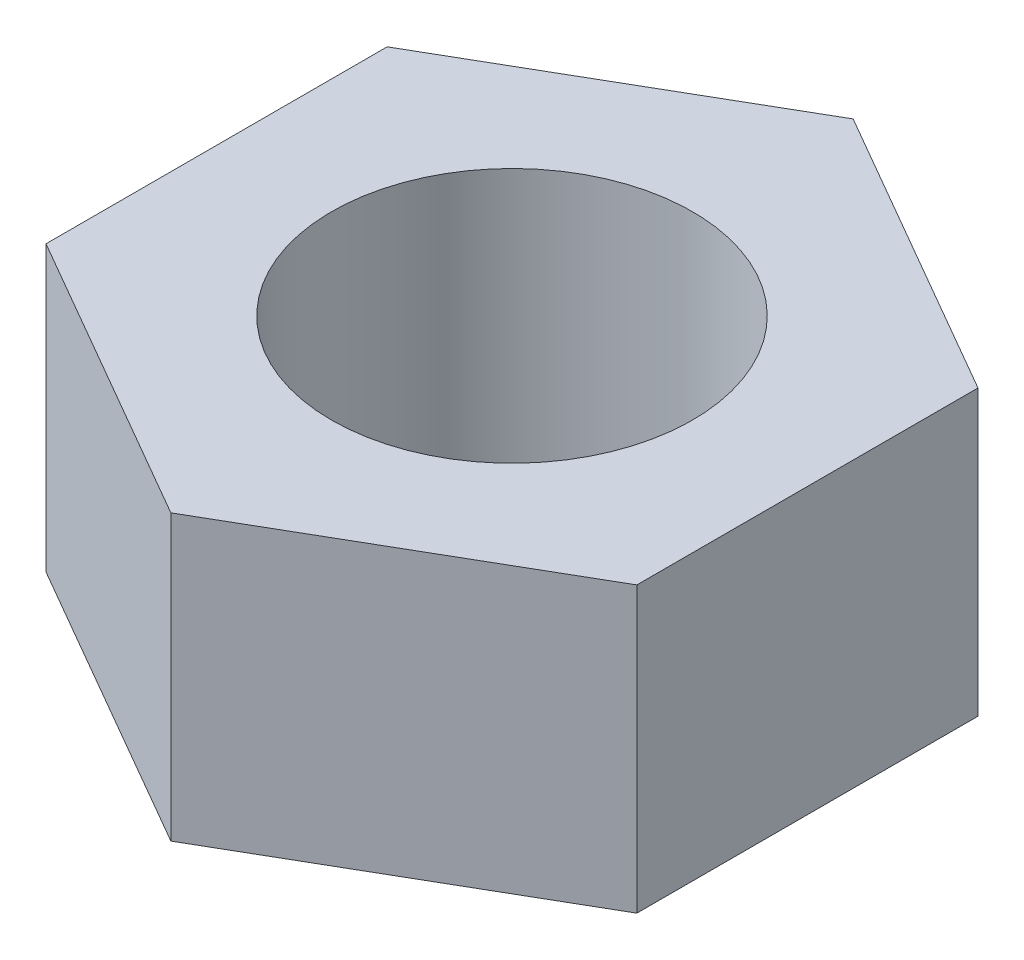
SolidWorks part; units mm, degrees
ref_plane "Front Plane" through (0, 0, 0) normal (0, 0, 1) x (1, 0, 0)
ref_plane "Top Plane" through (0, 0, 0) normal (0, 1, 0) x (1, 0, 0)
ref_plane "Right Plane" through (0, 0, 0) normal (1, 0, 0) x (0, 0, -1)
sketch "Sketch1" plane through (0, 0, 0) normal (0, 1, 0) x (1, 0, 0)
  line L1 (0, 6) -> (-5.1962, 3)
  line L2 (-5.1962, 3) -> (-5.1962, -3)
  line L3 (-5.1962, -3) -> (0, -6)
  line L4 (0, -6) -> (5.1962, -3)
  line L5 (5.1962, -3) -> (5.1962, 3)
  line L6 (5.1962, 3) -> (0, 6)
  circle A0 centre (0, 0) radius 5.1962 construction
  circle A1 centre (0, 0) radius 3.175
  dimension "D2" = 6.35
  dimension "D1" = 6
extrude "Boss-Extrude1" add sketch "Sketch1" along normal blind 5
